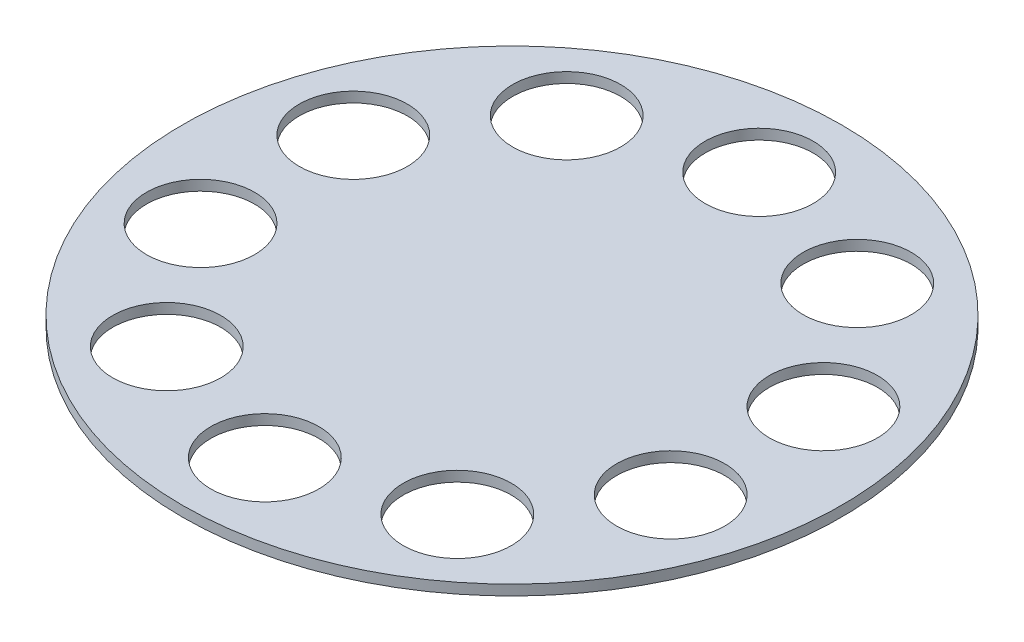
SolidWorks part; units mm, degrees
ref_plane "Front Plane" through (0, 0, 0) normal (0, 0, 1) x (1, 0, 0)
ref_plane "Top Plane" through (0, 0, 0) normal (0, 1, 0) x (1, 0, 0)
ref_plane "Right Plane" through (0, 0, 0) normal (1, 0, 0) x (0, 0, -1)
sketch "Sketch1" plane through (0, 0, 0) normal (0, 1, 0) x (1, 0, 0)
  circle A0 centre (0, 0) radius 203.2
  dimension "D1" = 406.4
extrude "Boss-Extrude1" add sketch "Sketch1" along normal blind 6.35
sketch "Sketch2" plane through (0, 6.35, 0) normal (0, 1, 0) x (1, 0, 0)
  circle A0 centre (0, 152.4) radius 33.3375
  circle A1 centre (89.5785, 123.2942) radius 33.3375
  circle A2 centre (144.941, 47.0942) radius 33.3375
  circle A3 centre (144.941, -47.0942) radius 33.3375
  circle A4 centre (89.5785, -123.2942) radius 33.3375
  circle A5 centre (0, -152.4) radius 33.3375
  circle A6 centre (-89.5785, -123.2942) radius 33.3375
  circle A7 centre (-144.941, -47.0942) radius 33.3375
  circle A8 centre (-144.941, 47.0942) radius 33.3375
  circle A9 centre (-89.5785, 123.2942) radius 33.3375
  point P24 (0, 0)
  dimension "D1" = 152.4
  dimension "D3" = 66.675
  dimension "D2" = 10
extrude "Cut-Extrude1" cut sketch "Sketch2" against normal through all
